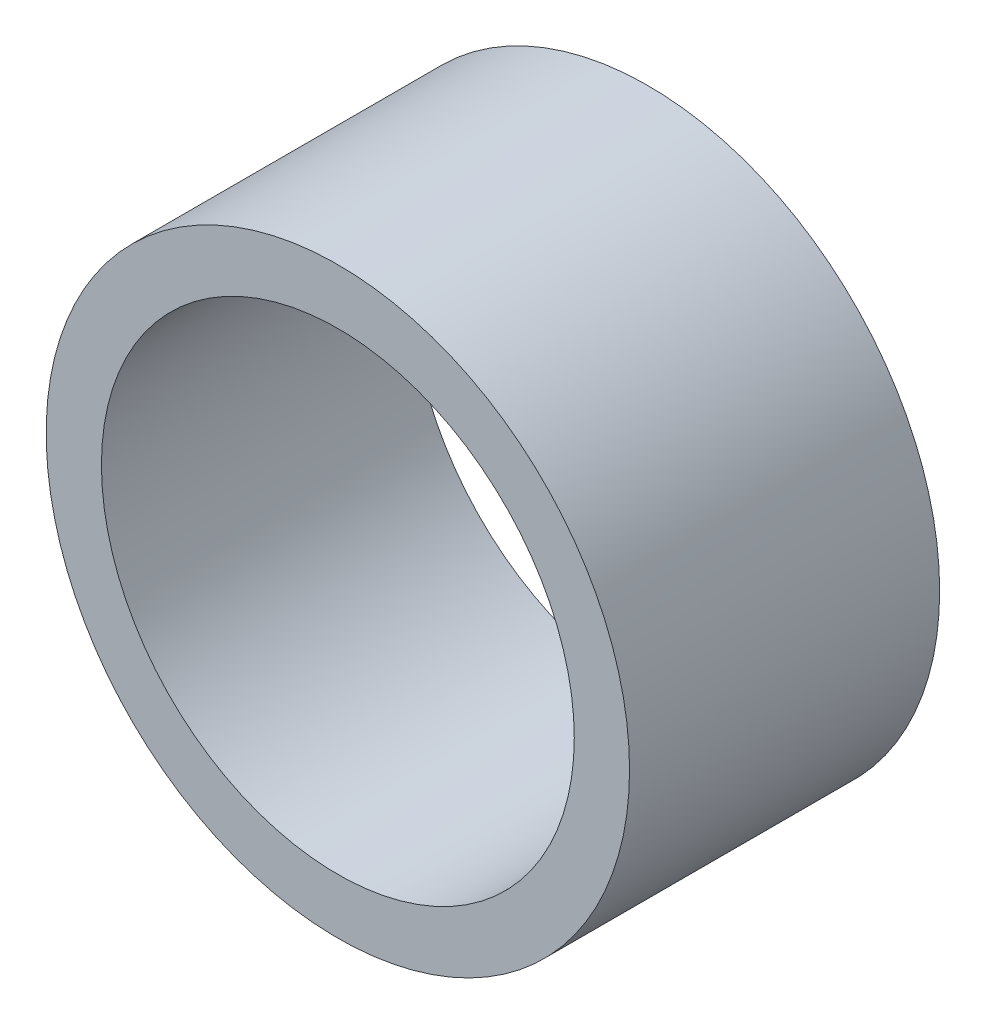
SolidWorks part; units mm, degrees
ref_plane "Front Plane" through (0, 0, 0) normal (0, 0, 1) x (1, 0, 0)
ref_plane "Top Plane" through (0, 0, 0) normal (0, 1, 0) x (1, 0, 0)
ref_plane "Right Plane" through (0, 0, 0) normal (1, 0, 0) x (0, 0, -1)
sketch "Sketch2" plane through (0, 0, 0) normal (0, 0, 1) x (1, 0, 0)
  circle A0 centre (0, 0) radius 9.5
  circle A1 centre (0, 0) radius 7.7
  dimension "D1" = 15.4
  dimension "D2" = 19
extrude "Boss-Extrude1" add sketch "Sketch2" against normal blind 10.1
